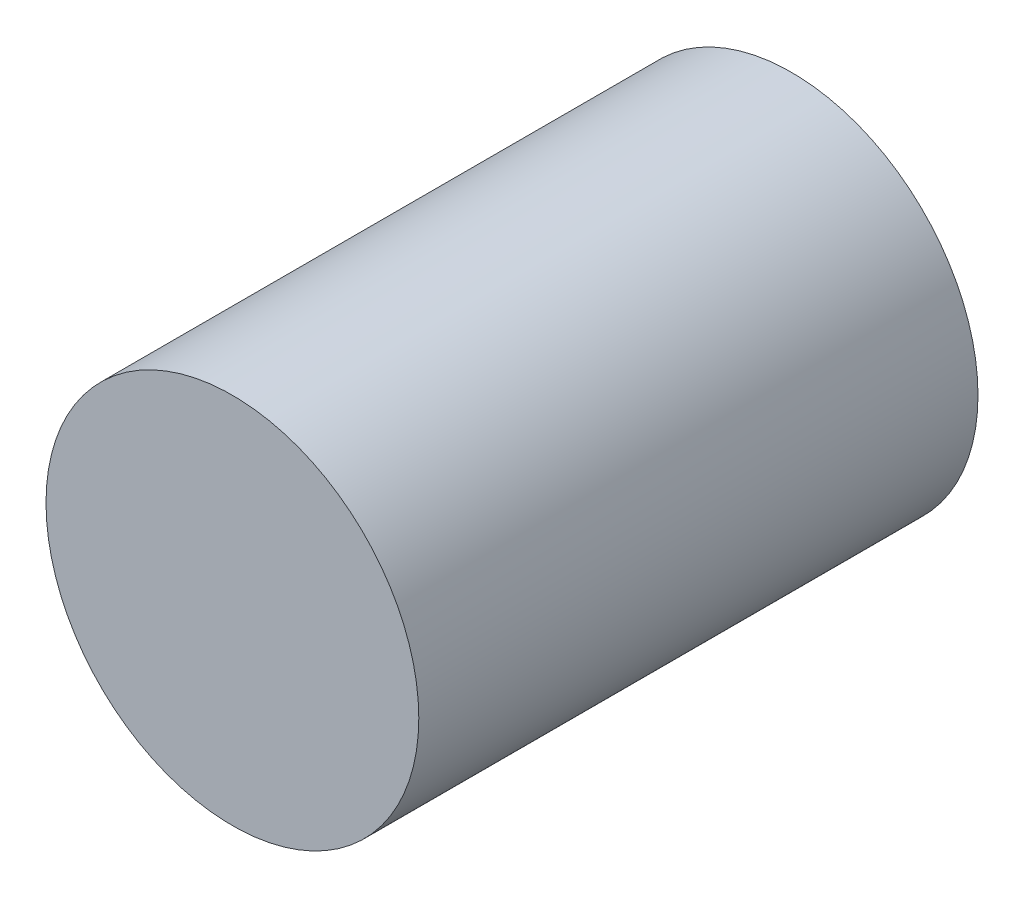
SolidWorks part; units mm, degrees
ref_plane "Спереди" through (0, 0, 0) normal (0, 0, 1) x (1, 0, 0)
ref_plane "Сверху" through (0, 0, 0) normal (0, 1, 0) x (1, 0, 0)
ref_plane "Справа" through (0, 0, 0) normal (1, 0, 0) x (0, 0, -1)
other "Configuration Table"
sketch "Эскиз1" plane through (0, 0, 0) normal (0, 0, 1) x (1, 0, 0)
  circle A0 centre (0, 0) radius 10
  dimension "D1" = 20
extrude "Бобышка-Вытянуть1" add sketch "Эскиз1" along normal blind 30
